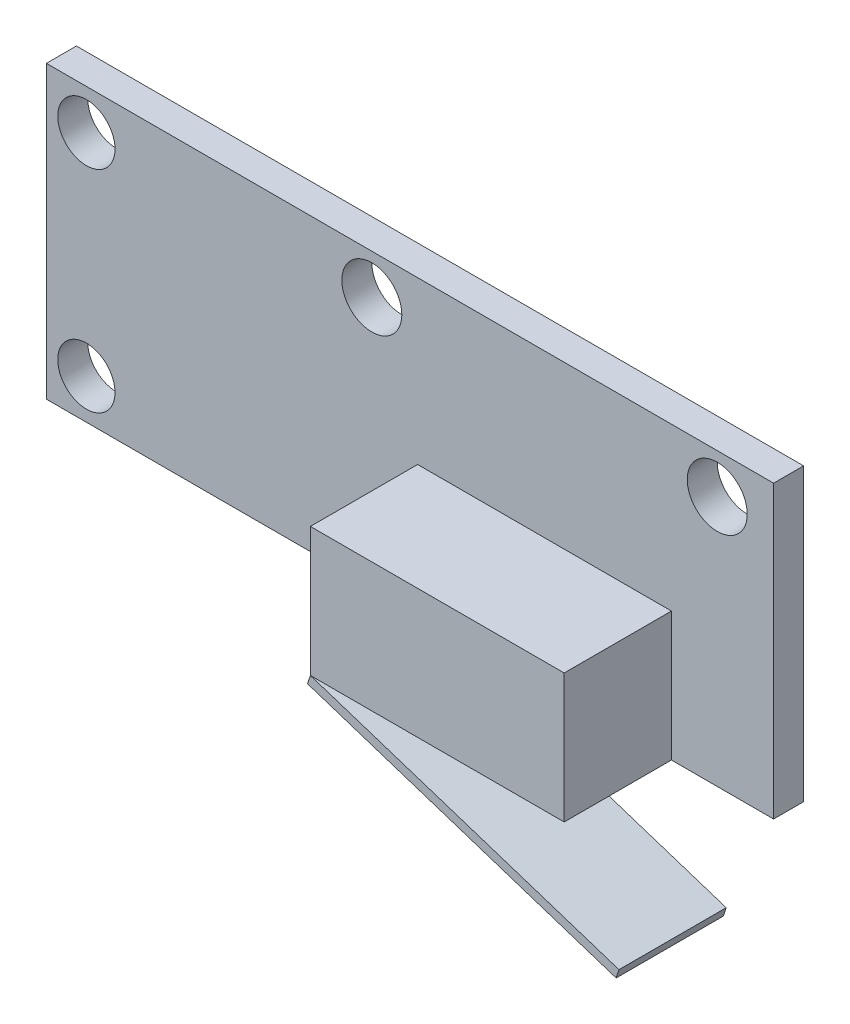
SolidWorks part; units mm, degrees
ref_plane "Piano frontale" through (0, 0, 0) normal (0, 0, 1) x (1, 0, 0)
ref_plane "Piano superiore" through (0, 0, 0) normal (0, 1, 0) x (1, 0, 0)
ref_plane "Piano destro" through (0, 0, 0) normal (1, 0, 0) x (0, 0, -1)
sketch "Schizzo1" plane through (0, 0, 0) normal (0, 0, 1) x (1, 0, 0)
  line L0 (40, 13.8) -> (0, 13.8) construction
  line L1 (0, 0) -> (40, 0)
  line L2 (0, 0) -> (0, 16)
  line L3 (0, 16) -> (40, 16)
  line L4 (40, 0) -> (40, 16)
  line L5 (2.2, 18.0305) -> (2.2, -3.4999) construction
  line L6 (0, 8) -> (40, 8) construction
  circle A0 centre (36.9, 13.8) radius 1.65
  circle A1 centre (17.9, 13.8) radius 1.65
  circle A2 centre (2.2, 13.8) radius 1.575
  circle A3 centre (2.2, 2.2) radius 1.575
  dimension "D4" = 3.1
  dimension "D5" = 3.3
  dimension "D1" = 40
  dimension "D2" = 16
  dimension "D3" = 19
  dimension "D6" = 2.2
  dimension "D7" = 2.2
extrude "Estrusione-Estrusione1" add sketch "Schizzo1" along normal blind 1.65
sketch "Schizzo2" plane through (0, 0, 1.65) normal (0, 0, 1) x (1, 0, 0)
  line L0 (27.4, 18.424) -> (27.4, -4.1046) construction
  line L2 (34.3808, 0) -> (20.4192, 0)
  line L3 (34.3808, 0) -> (34.3808, 7.0993)
  line L4 (34.3808, 7.0993) -> (20.4192, 7.0993)
  line L5 (20.4192, 0) -> (20.4192, 7.0993)
  line L6 (34.3808, 0) -> (20.4192, 7.0993) construction
  line L7 (34.3808, 7.0993) -> (20.4192, 0) construction
  line L8 (0, 0) -> (40, 0) construction
  circle A0 centre (36.9, 13.8) radius 1.65 construction
  circle A1 centre (17.9, 13.8) radius 1.65 construction
  point P6 (27.4, 3.5497)
extrude "Estrusione-Estrusione2" add sketch "Schizzo2" along normal blind 5.9
sketch "Schizzo3" plane through (0, 0, 1.65) normal (0, 0, 1) x (1, 0, 0)
  line L0 (20.4192, 0) -> (37.3941, -5.5271)
extrude "Estrusione-Sottile1" add sketch "Schizzo3" along normal blind 5.9 separate body thin
